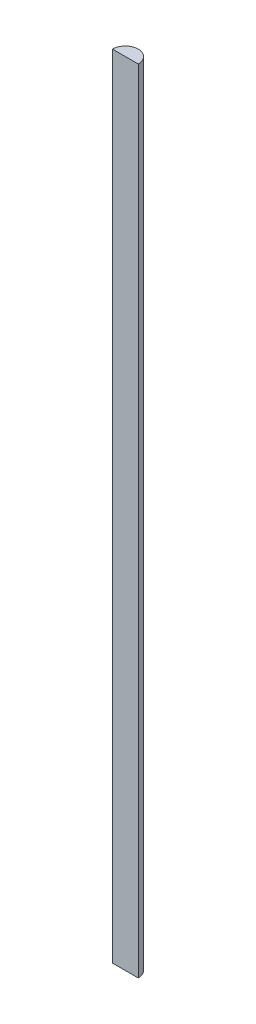
SolidWorks part; units mm, degrees
ref_plane "Plano frontal" through (0, 0, 0) normal (0, 0, 1) x (1, 0, 0)
ref_plane "Plano superior" through (0, 0, 0) normal (0, 1, 0) x (1, 0, 0)
ref_plane "Plano direito" through (0, 0, 0) normal (1, 0, 0) x (0, 0, -1)
sketch "Esboço1" plane through (0, 0, 0) normal (0, 1, 0) x (1, 0, 0)
  line L0 (-2.45, 0) -> (2.45, 0)
  arc A0 (2.45, 0) -> (-2.45, 0) centre (0, 0) ccw
  point P5 (0, 0)
extrude "Ressalto-extrusão1" add sketch "Esboço1" along normal blind 150 contours L0 A0
